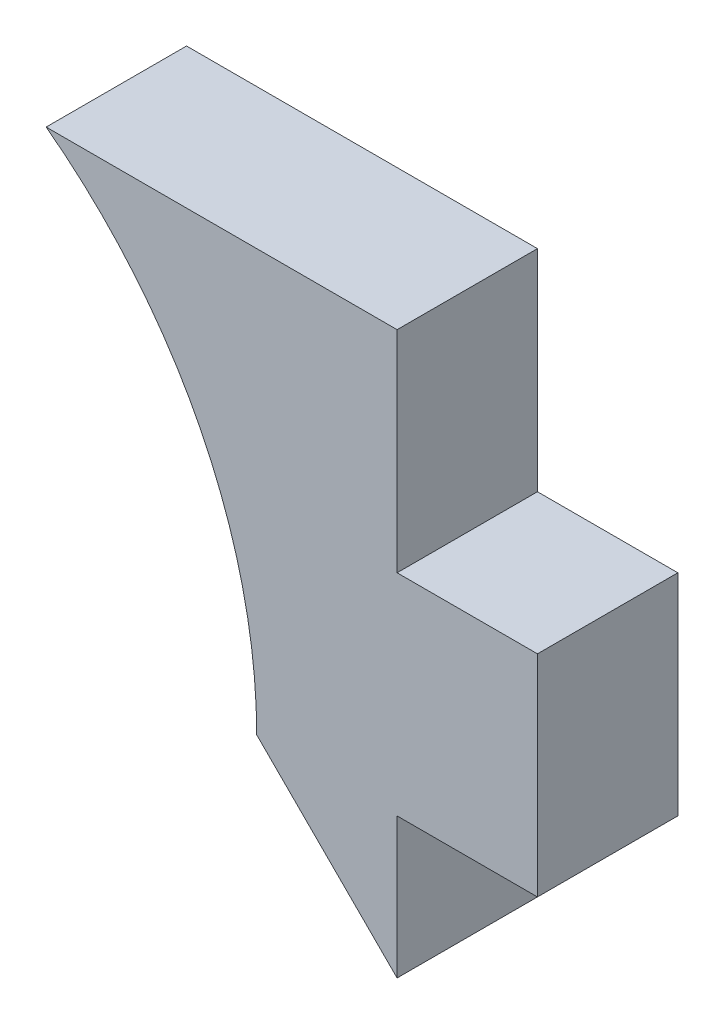
SolidWorks part; units mm, degrees
ref_plane "Front Plane" through (0, 0, 0) normal (0, 0, 1) x (1, 0, 0)
ref_plane "Top Plane" through (0, 0, 0) normal (0, 1, 0) x (1, 0, 0)
ref_plane "Right Plane" through (0, 0, 0) normal (1, 0, 0) x (0, 0, -1)
sketch "Sketch1" plane through (0, 0, 0) normal (0, 0, 1) x (1, 0, 0)
  line L1692 (494, 6) -> (494, 3)
  line L1693 (494, 3) -> (491, 6)
  line L1694 (486.5, 15) -> (494, 15)
  line L1695 (494, 15) -> (494, 10.5)
  line L1696 (494, 10.5) -> (497, 10.5)
  line L1697 (497, 10.5) -> (497, 6)
  line L1698 (497, 6) -> (494, 6)
  arc A4 (491, 6) -> (486.5, 15) centre (479.75, 6) ccw
extrude "Boss-Extrude1" add sketch "Sketch1" along normal blind 3
